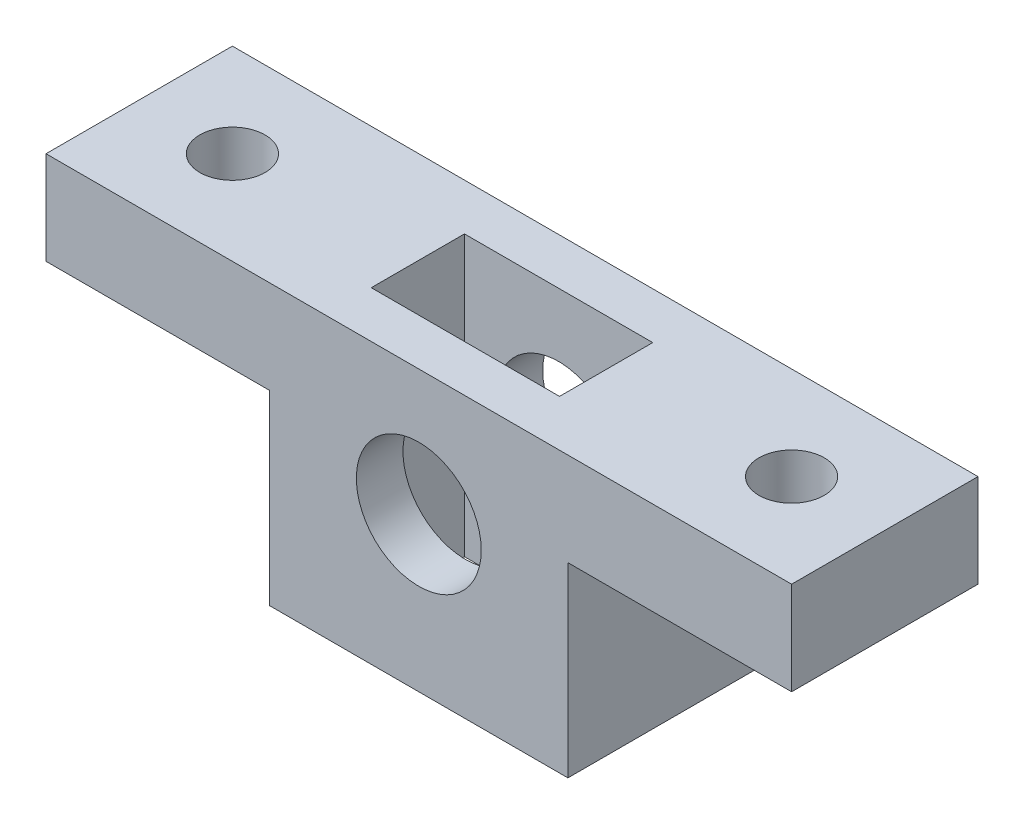
SolidWorks part; units mm, degrees
ref_plane "Plano frontal" through (0, 0, 0) normal (0, 0, 1) x (1, 0, 0)
ref_plane "Plano superior" through (0, 0, 0) normal (0, 1, 0) x (1, 0, 0)
ref_plane "Plano direito" through (0, 0, 0) normal (1, 0, 0) x (0, 0, -1)
sketch "Esboço1" plane through (0, 0, 0) normal (0, 0, 1) x (1, 0, 0)
  line L1 (0, -0.9765) -> (-5, -3.8632) construction
  line L2 (-8, -5) -> (-8, -15)
  line L3 (-8, -15) -> (8, -15)
  line L4 (8, -5) -> (8, -15)
  line L5 (-5, -3.8632) -> (-5, -9.6368) construction
  line L6 (-5, -9.6368) -> (0, -12.5235) construction
  line L7 (-20, 0) -> (-20, -5)
  line L8 (-20, -5) -> (-8, -5)
  line L9 (0, 0) -> (0, -15) construction
  line L10 (20, 0) -> (20, -5)
  line L11 (-20, 0) -> (20, 0)
  line L12 (20, -5) -> (8, -5)
  line L13 (0, -12.5235) -> (5, -9.6368) construction
  line L14 (5, -9.6368) -> (5, -3.8632) construction
  line L15 (5, -3.8632) -> (0, -0.9765) construction
  circle A0 centre (0, -6.75) radius 3.35
  circle A1 centre (0, -6.75) radius 5 construction
  point P0 (0, 0)
  dimension "D5" = 15
  dimension "D6" = 6.7
  dimension "D3" = 6.75
  dimension "D1" = 40
  dimension "D2" = 16
  dimension "D4" = 5
  dimension "D7" = 10
extrude "Ressalto-extrusão1" add sketch "Esboço1" along normal blind 10
sketch "Esboço2" plane through (0, 0, 0) normal (0, 1, 0) x (1, 0, 0)
  line L0 (0, 0) -> (0, -10) construction
  line L1 (20, -10) -> (-20, -10) construction
  circle A0 centre (-15, -5) radius 1.75
  circle A1 centre (15, -5) radius 1.75
  point P8 (0, -5)
  dimension "D1" = 15
  dimension "D2" = 3.5
extrude "Corte-extrusão1" cut sketch "Esboço2" against normal blind 10
sketch "Esboço3" plane through (0, -15, 0) normal (0, -1, 0) x (1, 0, 0)
  line L0 (0, 10) -> (0, 0) construction
  line L1 (-8, 10) -> (8, 10) construction
  line L2 (-8, 0) -> (8, 0) construction
  line L4 (-5.05, 7.5) -> (5.05, 7.5)
  line L5 (-5.05, 7.5) -> (-5.05, 2.5)
  line L6 (-5.05, 2.5) -> (5.05, 2.5)
  line L7 (5.05, 7.5) -> (5.05, 2.5)
  line L8 (-5.05, 7.5) -> (5.05, 2.5) construction
  line L9 (-5.05, 2.5) -> (5.05, 7.5) construction
  point P6 (0, 5)
  dimension "D1" = 10.1
  dimension "D2" = 5
extrude "Corte-extrusão2" cut sketch "Esboço3" against normal blind 20
